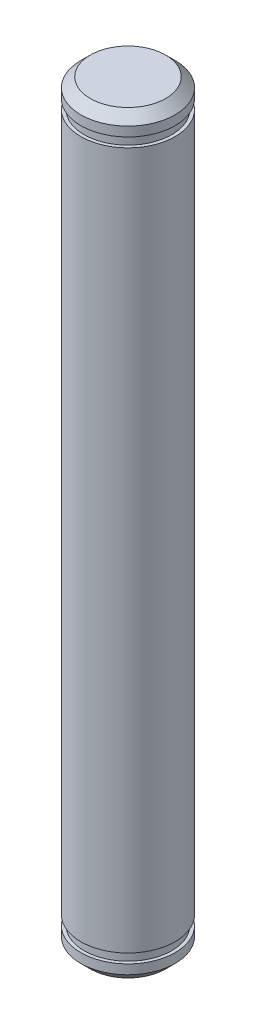
SolidWorks part; units mm, degrees
ref_plane "前视基准面" through (0, 0, 0) normal (0, 0, 1) x (1, 0, 0)
ref_plane "上视基准面" through (0, 0, 0) normal (0, 1, 0) x (1, 0, 0)
ref_plane "右视基准面" through (0, 0, 0) normal (1, 0, 0) x (0, 0, -1)
other "Configuration Table"
sketch "草图1" plane through (0, 0, 0) normal (0, 0, 1) x (1, 0, 0)
  line L0 (0, 17.9143) -> (0, -10.0949) construction
  line L1 (0, 40) -> (5, 40)
  line L2 (5, 40) -> (5, 30)
  line L4 (5, 30) -> (5, -30)
  line L6 (5, -30) -> (5, -40)
  line L7 (5, -40) -> (0, -40)
  line L8 (0, 0) -> (25.4592, 0) construction
  line L9 (0, 40) -> (0, -40)
  dimension "D1" = 5
  dimension "D3" = 60
  dimension "D4" = 10
  dimension "D5" = 10
revolve "旋转1" add sketch "草图1" angle 360 about L9
chamfer "倒角1" distance 1 angle 45 2 edges at (-5, -40, 0) (-5, 40, 0)
ref_plane "基准面1" through (0, 0, 0) normal (0, 1, 0) x (1, 0, 0)
sketch "草图2" plane through (0, 40, 0) normal (0, 1, 0) x (1, 0, 0)
  circle A0 centre (0, 0) radius 5 construction
  circle A1 centre (0, 0) radius 5
  circle A2 centre (0, 0) radius 4.65
  dimension "D1" = 9.3
extrude "切除-拉伸1" cut sketch "草图2" along normal blind 1 from offset 3 offset against normal yes
mirror "镜向1" about plane through (0, 0, 0) normal (0, 1, 0) of "切除-拉伸1"
